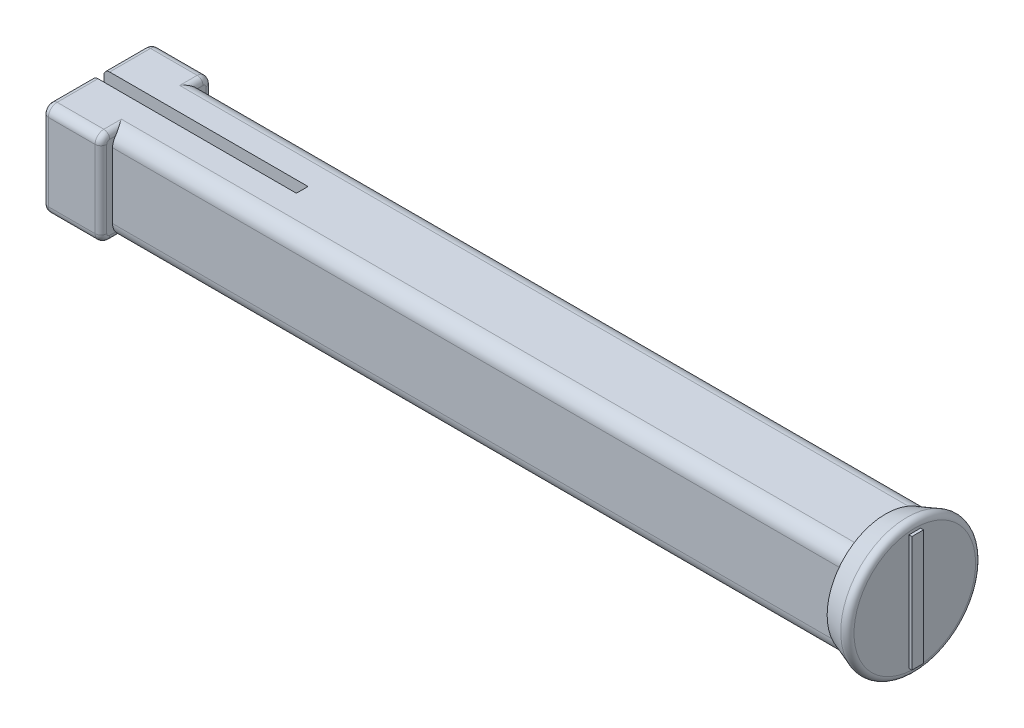
SolidWorks part; units mm, degrees
ref_plane "Plan de face" through (0, 0, 0) normal (0, 0, 1) x (1, 0, 0)
ref_plane "Plan de dessus" through (0, 0, 0) normal (0, 1, 0) x (1, 0, 0)
ref_plane "Plan de droite" through (0, 0, 0) normal (1, 0, 0) x (0, 0, -1)
sketch "Esquisse1" plane through (0, 0, 0) normal (0, 0, 1) x (1, 0, 0)
  line L1 (-7.4184, 1.956) -> (19.5816, 1.956)
  line L2 (-7.4184, 1.956) -> (-7.4184, -1.294)
  line L3 (-7.4184, -1.294) -> (19.5816, -1.294)
  line L4 (19.5816, 1.956) -> (19.5816, -1.294)
  dimension "D1" = 27
  dimension "D2" = 3.25
extrude "Boss.-Extru.5" add sketch "Esquisse1" along normal blind 3.8
ref_plane "Plan1" through (-7.4184, 1.956, 0) normal (-1, 0, 0) x (0, 0, 1)
sketch "Esquisse10" plane through (0, 0, 0) normal (0, 0, -1) x (-1, 0, 0)
  line L0 (7.4184, -1.294) -> (-19.5816, -1.294) construction
  line L1 (-19.5816, 1.956) -> (5.4184, 1.956)
  line L2 (-19.5816, 1.956) -> (-19.5816, -1.294)
  line L3 (-19.5816, -1.294) -> (5.4184, -1.294)
  line L4 (5.4184, 1.956) -> (5.4184, -1.294)
  dimension "D1" = 25
extrude "Enlèv. mat.-Extru.1" cut sketch "Esquisse10" against normal blind 0.4
sketch "Esquisse12" plane through (0, 0, 3.8) normal (0, 0, 1) x (1, 0, 0)
  line L0 (19.5816, 1.956) -> (-7.4184, 1.956) construction
  line L1 (-5.4184, 1.956) -> (19.5816, 1.956)
  line L2 (-5.4184, 1.956) -> (-5.4184, -1.294)
  line L3 (-5.4184, -1.294) -> (19.5816, -1.294)
  line L4 (19.5816, 1.956) -> (19.5816, -1.294)
  dimension "D1" = 25
extrude "Enlèv. mat.-Extru.2" cut sketch "Esquisse12" against normal blind 0.4
sketch "Esquisse13" plane through (-7.4184, 0, 0) normal (-1, 0, 0) x (0, 0, 1)
  line L8 (1.3, 1.456) -> (2.5, 1.456)
  line L9 (0.8, 1.456) -> (1.3, 1.456)
  line L10 (0.8, 1.456) -> (0.8, 0.956)
  line L11 (0.8, 0.956) -> (1.3, 0.956)
  line L12 (1.3, 1.456) -> (1.3, 0.956)
  line L13 (3, 1.456) -> (2.5, 1.456)
  line L14 (3, 1.456) -> (3, 0.956)
  line L15 (3, 0.956) -> (2.5, 0.956)
  line L16 (2.5, 1.456) -> (2.5, 0.956)
  line L17 (0.8, -0.794) -> (1.3, -0.794)
  line L18 (0.8, -0.794) -> (0.8, -0.294)
  line L19 (0.8, -0.294) -> (1.3, -0.294)
  line L20 (1.3, -0.794) -> (1.3, -0.294)
  line L21 (3, -0.794) -> (2.5, -0.794)
  line L22 (3, -0.794) -> (3, -0.294)
  line L23 (3, -0.294) -> (2.5, -0.294)
  line L24 (2.5, -0.794) -> (2.5, -0.294)
  line L25 (3, 0.956) -> (3, -0.294)
  line L26 (2.5, -0.794) -> (1.3, -0.794)
  line L27 (0.8, 0.956) -> (0.8, -0.294)
  arc A0 (1.3, 1.456) -> (0.8, 0.956) centre (1.3, 0.956) ccw
  arc A1 (1.3, -0.794) -> (0.8, -0.294) centre (1.3, -0.294) cw
  arc A2 (3, -0.294) -> (2.5, -0.794) centre (2.5, -0.294) cw
  arc A3 (3, 0.956) -> (2.5, 1.456) centre (2.5, 0.956) ccw
  dimension "D5" = 0.5
  dimension "D6" = 0.5
  dimension "D7" = 0.5
  dimension "D8" = 0.5
  dimension "D9" = 0.5
  dimension "D10" = 0.5
  dimension "D11" = 0.5
  dimension "D12" = 0.5
extrude "Enlèv. mat.-Extru.3" cut sketch "Esquisse13" against normal up to surface (27 mm away) contours L25 A2 L26 A1 L27 A0 L8 A3 up to face at (19.5816, 0.331, 1.9)
sketch "Esquisse14" plane through (0, 1.956, 0) normal (0, 1, 0) x (1, 0, 0)
  line L0 (-7.4184, -3.8) -> (-7.4184, 0) construction
  line L1 (-7.4184, -1.7) -> (-0.4184, -1.7)
  line L2 (-7.4184, -1.7) -> (-7.4184, -2.1)
  line L3 (-7.4184, -2.1) -> (-0.4184, -2.1)
  line L4 (-0.4184, -1.7) -> (-0.4184, -2.1)
  line L5 (-5.4184, 0) -> (-7.4184, 0) construction
  line L7 (-5.4184, -3.8) -> (-7.4184, -3.8) construction
  dimension "D1" = 1.7
  dimension "D2" = 1.7
  dimension "D3" = 7
extrude "Enlèv. mat.-Extru.4" cut sketch "Esquisse14" against normal through all
fillet "Congé1" radius 0.5 4 edges at (7.0816, -1.294, 3.4) (7.0816, 1.956, 3.4) (7.0816, -1.294, 0.4) (7.0816, 1.956, 0.4)
fillet "Congé2" radius 0.3 4 edges at (-6.4184, -1.294, 0) (-6.4184, 1.956, 0) (-6.4184, 1.956, 3.8) (-6.4184, -1.294, 3.8)
fillet "Congé3" radius 0.2 20 edges at (-5.4184, 1.956, 3.2) (-5.4184, 1.8681, 3.7121) (-5.4184, -1.294, 3.2) (-5.4184, -1.2061, 3.7121) (-7.4184, 1.956, 2.8) (-7.4184, 1.8681, 3.7121) (-7.4184, -1.294, 2.8) (-7.4184, -1.2061, 3.7121) (-7.4184, 1.956, 1) (-7.4184, 1.8681, 0.0879) (-7.4184, -1.294, 1) (-7.4184, -1.2061, 0.0879) (-5.4184, -1.294, 0.6) (-5.4184, -1.2061, 0.0879) (-5.4184, 1.956, 0.6) (-5.4184, 1.8681, 0.0879) (-5.4184, 0.331, 3.8) (-7.4184, 0.331, 3.8) (-7.4184, 0.331, 0) (-5.4184, 0.331, 0)
sketch "Esquisse19" plane through (19.5816, 0, 0) normal (1, 0, 0) x (0, 0, -1)
  circle A2 centre (-1.9, 0.331) radius 2.0052
extrude "Boss.-Extru.8" add sketch "Esquisse19" along normal blind 1
draft "Dépouille1" type of draft neutral plane draft angle 20 faces to draft 1 face at (20.5816, 0.331, -0.1052) neutral plane through (19.5816, 0.331, 1.9) neutral plane normal (-1, 0, 0) parameters "D1"=20
fillet "Congé4" radius 0.2 1 edges at (20.5816, 0.331, -0.4692)
sketch "Esquisse20" plane through (20.5816, 0, 0) normal (1, 0, 0) x (0, 0, -1)
  line L0 (-1.9, 2.4145) -> (-1.9, -1.7525)
  line L2 (-2.1, 2.3145) -> (-1.7, 2.3145)
  line L3 (-2.1, 2.3145) -> (-2.1, -1.6525)
  line L4 (-2.1, -1.6525) -> (-1.7, -1.6525)
  line L5 (-1.7, 2.3145) -> (-1.7, -1.6525)
  arc A0 (-3.4511, 1.7222) -> (0.0561, 1.0486) centre (-1.9, 0.331) ccw
  circle A1 centre (-1.9, 0.331) radius 2.0835 construction
  circle A2 centre (-1.9, 0.331) radius 2.0835
  dimension "D7" = 4.1671
  dimension "D1" = 0.2
  dimension "D2" = 0.2
  dimension "D3" = 0.2
  dimension "D4" = 0.1
  dimension "D5" = 0.1
  dimension "D6" = 0.1
extrude "Boss.-Extru.9" add sketch "Esquisse20" along normal blind 0.1 contours L2 L5 L4 L3
